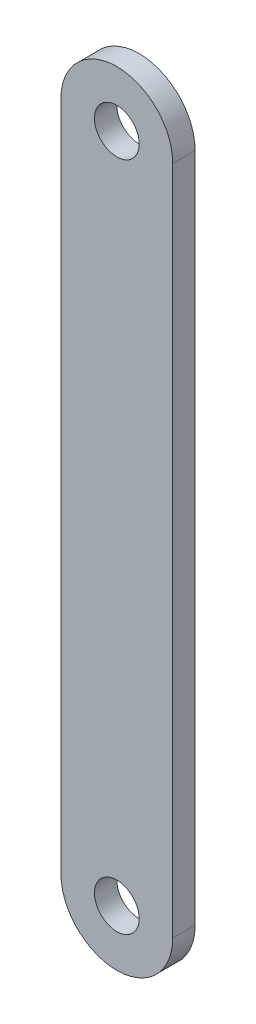
SolidWorks part; units mm, degrees
ref_plane "Alzado" through (0, 0, 0) normal (0, 0, 1) x (1, 0, 0)
ref_plane "Planta" through (0, 0, 0) normal (0, 1, 0) x (1, 0, 0)
ref_plane "Vista lateral" through (0, 0, 0) normal (1, 0, 0) x (0, 0, -1)
sketch "Croquis1" plane through (0, 0, 0) normal (0, 0, 1) x (1, 0, 0)
  line L0 (0, 0) -> (50, 0) construction
  line L1 (50, 0) -> (50, 300)
  line L2 (50, 300) -> (0, 300) construction
  line L3 (0, 300) -> (0, 0)
  arc A0 (0, 0) -> (50, 0) centre (25, 0) ccw
  arc A1 (50, 300) -> (0, 300) centre (25, 300) ccw
  circle A2 centre (25, 300) radius 10
  circle A3 centre (25, 0) radius 10
  dimension "D3" = 20
  dimension "D4" = 20
  dimension "D1" = 50
  dimension "D2" = 300
extrude "Saliente-Extruir1" add sketch "Croquis1" along normal blind 10
